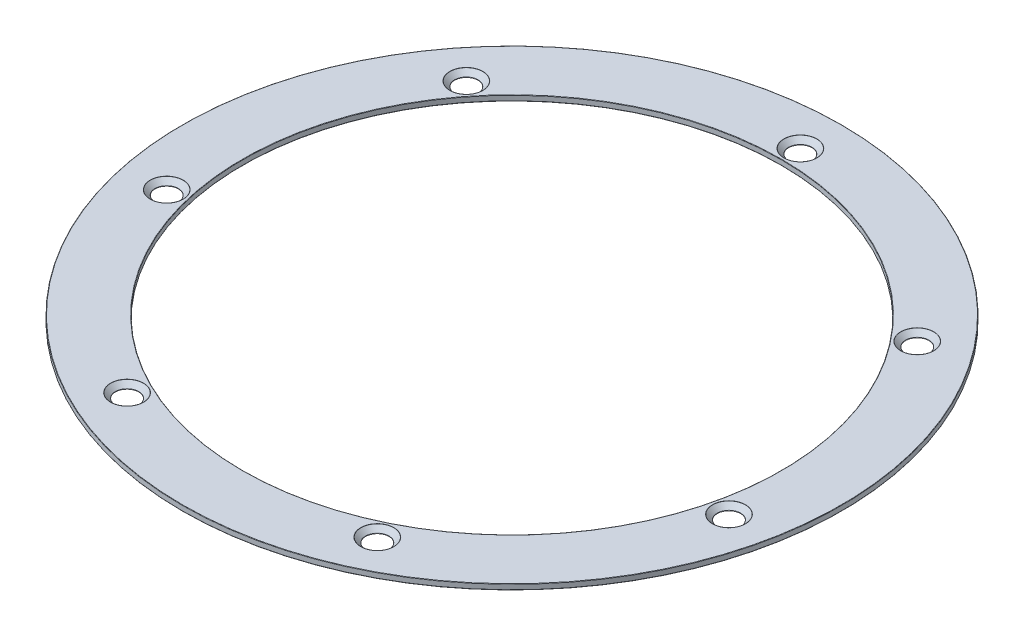
SolidWorks part; units mm, degrees
material "1.4301 (X5CrNi18-10)"
ref_plane "Ebene vorne" through (0, 0, 0) normal (0, 0, 1) x (1, 0, 0)
ref_plane "Ebene oben" through (0, 0, 0) normal (0, 1, 0) x (1, 0, 0)
ref_plane "Ebene rechts" through (0, 0, 0) normal (1, 0, 0) x (0, 0, -1)
sketch "Skizze1" plane through (0, 0, 0) normal (0, 1, 0) x (1, 0, 0)
  circle A0 centre (0, 0) radius 75.2
  circle A1 centre (0, 0) radius 92
  dimension "D1" = 150.4
  dimension "D2" = 184
extrude "Aufsatz-Linear austragen1" add sketch "Skizze1" along normal blind 1.5
hole_wizard "Formsenkung für M4 Senkschraube mit Innensechskant1" positions "Skizze5" profile "Skizze6" countersink size "M4" standard "DIN" end condition through all
sketch "Skizze5" plane through (0, 1.5, 0) normal (0, 1, 0) x (1, 0, 0)
  point P0 (0, 80.5)
  dimension "D1" = 80.5
sketch "Skizze6" plane through (0, 1.5, -80.5) normal (1, 0, 0) x (0, 0, 1)
  line L0 (0, 0) -> (0, 1.5)
  line L1 (0, 1.5) -> (2.25, 1.5)
  line L2 (2.25, 1.5) -> (2.25, 2.34)
  line L3 (2.25, 2.34) -> (4.59, 0)
  line L5 (4.59, 0) -> (0, 0)
  line L6 (-2.25, 2.34) -> (-4.59, 0) construction
  line L11 (0, -6.35) -> (0, 107.95) construction
  dimension "Bohrerdurchmesser" = 4.5
  dimension "Bohrungstiefe" = 1.5
  dimension "Senkdurchmesser (Oben)" = 9.18
  dimension "Senkwinkel (Oben)" = 90
pattern_circular "Kreismuster1" count 7 over 360 about axis through (0, 0, 0) along (0, 1, 0) of "Formsenkung für M4 Senkschraube mit Innensechskant1"
fillet "Verrundung1" radius 0.1 18 edges at (0, 0, 75.2) (0, 0, 92) (0, 0, -77.41) (-60.5216, 0, -48.2643) (-75.4692, 0, 17.2253) (-33.5869, 0, 69.744) (33.5869, 0, 69.744) (75.4692, 0, 17.2253) (60.5216, 0, -48.2643) (0, 1.5, 75.2) (0, 1.5, 92) (0, 1.5, -75.91) (-59.3488, 1.5, -47.3291) (-74.0068, 1.5, 16.8916) (-32.9361, 1.5, 68.3925) (32.9361, 1.5, 68.3925) (74.0068, 1.5, 16.8916) (59.3488, 1.5, -47.3291)
